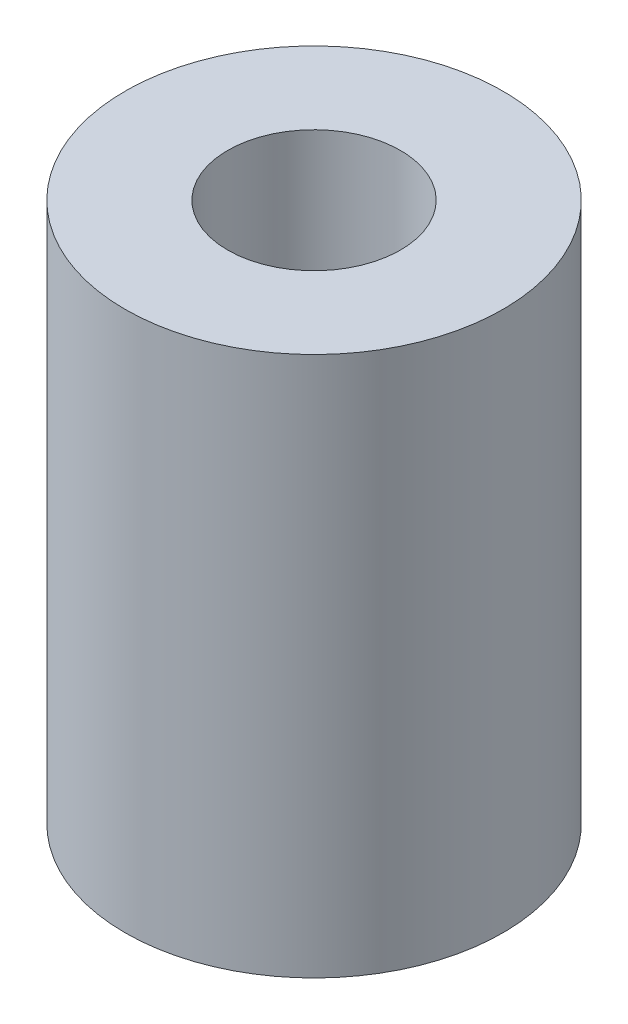
SolidWorks part; units mm, degrees
material "ABS"
ref_plane "Plano frontal" through (0, 0, 0) normal (0, 0, 1) x (1, 0, 0)
ref_plane "Plano superior" through (0, 0, 0) normal (0, 1, 0) x (1, 0, 0)
ref_plane "Plano direito" through (0, 0, 0) normal (1, 0, 0) x (0, 0, -1)
sketch "Esboço1" plane through (0, 0, 0) normal (0, 1, 0) x (1, 0, 0)
  circle A0 centre (0, 0) radius 1.6
  circle A1 centre (0, 0) radius 3.5
  dimension "D1" = 3.2
  dimension "D2" = 7
extrude "Ressalto-extrusão1" add sketch "Esboço1" along normal mid plane 10
